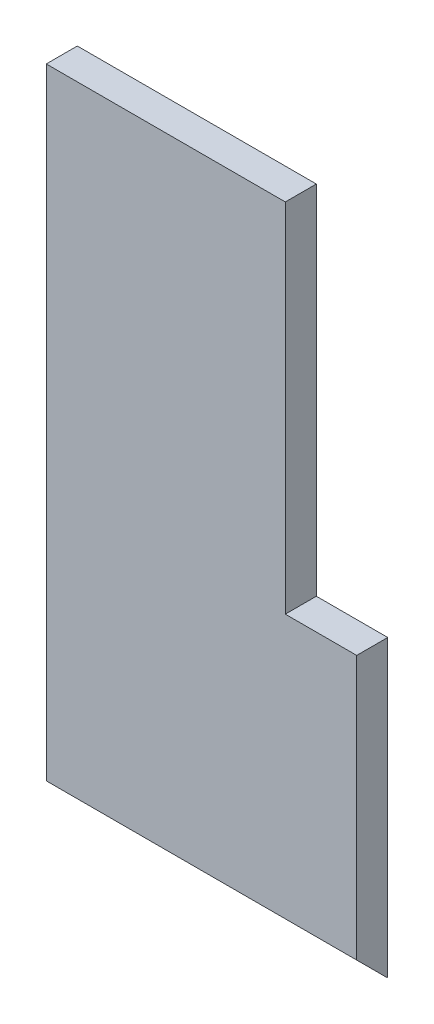
SolidWorks part; units mm, degrees
ref_plane "Plan de face" through (0, 0, 0) normal (0, 0, 1) x (1, 0, 0)
ref_plane "Plan de dessus" through (0, 0, 0) normal (0, 1, 0) x (1, 0, 0)
ref_plane "Plan de droite" through (0, 0, 0) normal (1, 0, 0) x (0, 0, -1)
sketch "Esquisse1" plane through (0, 0, 0) normal (0, 0, 1) x (1, 0, 0)
  line L0 (-50, 105) -> (27, 105)
  line L1 (-50, -105) -> (50, -105)
  line L2 (-50, -105) -> (-50, 105)
  line L3 (27, 105) -> (27, -10)
  line L4 (27, -10) -> (50, -10)
  line L5 (-50, -105) -> (50, 105) construction
  line L6 (-50, 105) -> (50, -105) construction
  line L7 (50, -10) -> (50, -105)
  point P0 (0, 0)
  dimension "D1" = 100
  dimension "D2" = 210
  dimension "D3" = 115
  dimension "D4" = 23
extrude "Boss.-Extru.1" add sketch "Esquisse1" along normal blind 10 contours L0 L3 L4 L7 L1 L2
ref_plane "Plan1" through (50, 0, 0) normal (1, 0, 0) x (0, 0, -1)
sketch "Esquisse2" plane through (50, 0, 0) normal (1, 0, 0) x (0, 0, -1)
  line L0 (-10, -105) -> (0, -105)
  line L1 (0, -105) -> (-10, -95)
  line L2 (-10, -10) -> (-10, -105) construction
  line L3 (-10, -95) -> (-10, -105)
  dimension "D1" = 45
extrude "Enlèv. mat.-Extru.1" cut sketch "Esquisse2" against normal blind 100 contours L1 L3 L0
